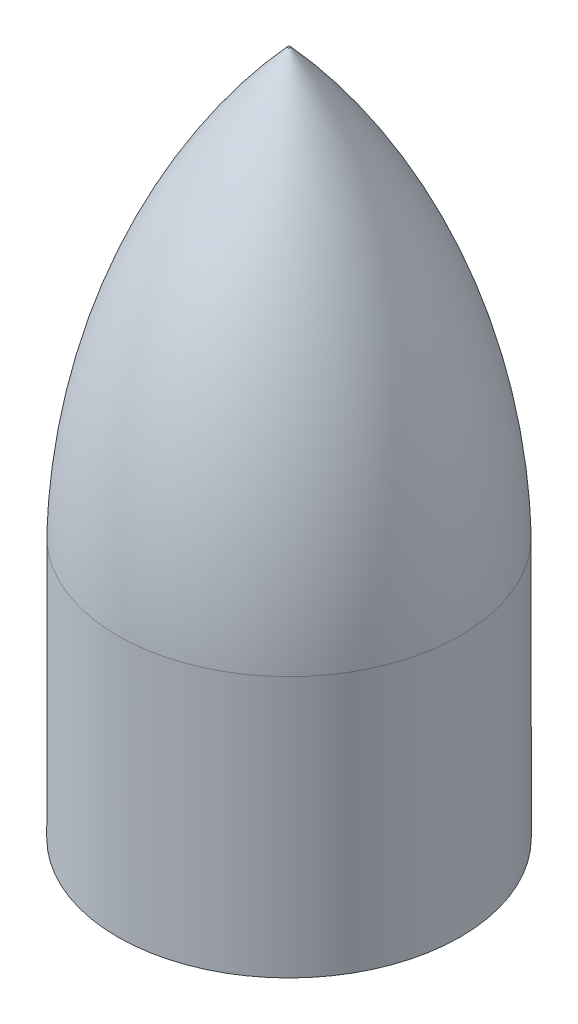
SolidWorks part; units mm, degrees
material "PVC 0.007 Plasticized"
ref_plane "Front Plane" through (0, 0, 0) normal (0, 0, 1) x (1, 0, 0)
ref_plane "Top Plane" through (0, 0, 0) normal (0, 1, 0) x (1, 0, 0)
ref_plane "Right Plane" through (0, 0, 0) normal (1, 0, 0) x (0, 0, -1)
sketch "Sketch1" plane through (0, 0, 0) normal (0, 1, 0) x (1, 0, 0)
  circle A0 centre (0, 0) radius 1.5
  dimension "D1" = 3
extrude "Boss-Extrude1" add sketch "Sketch1" along normal blind 6
sketch "Sketch2" plane through (0, 0, 0) normal (0, 0, 1) x (1, 0, 0)
  line L0 (0, 6) -> (0, 2) construction
  line L1 (1.5, 6) -> (-1.5, 6) construction
  line L3 (1.5, 0) -> (1.5, 6) construction
  line L9 (1.5, 2) -> (1.6691, 2)
  line L11 (1.6691, 2) -> (1.6691, 6.0847)
  line L12 (1.6691, 6.0847) -> (0.01, 6.0847)
  line L13 (0.01, 6.0847) -> (0.01, 6)
  arc A4 (0.01, 6) -> (1.5, 2) centre (-4.2312, 2.1426) cw
  dimension "D2" = 5.733
  dimension "D3" = 4.0847
  dimension "D1" = 4
  dimension "D4" = 1.6591
  dimension "D5" = 0.1691
  dimension "D6" = 1.5
revolve "Cut-Revolve2" cut sketch "Sketch2" angle 360 about L0
